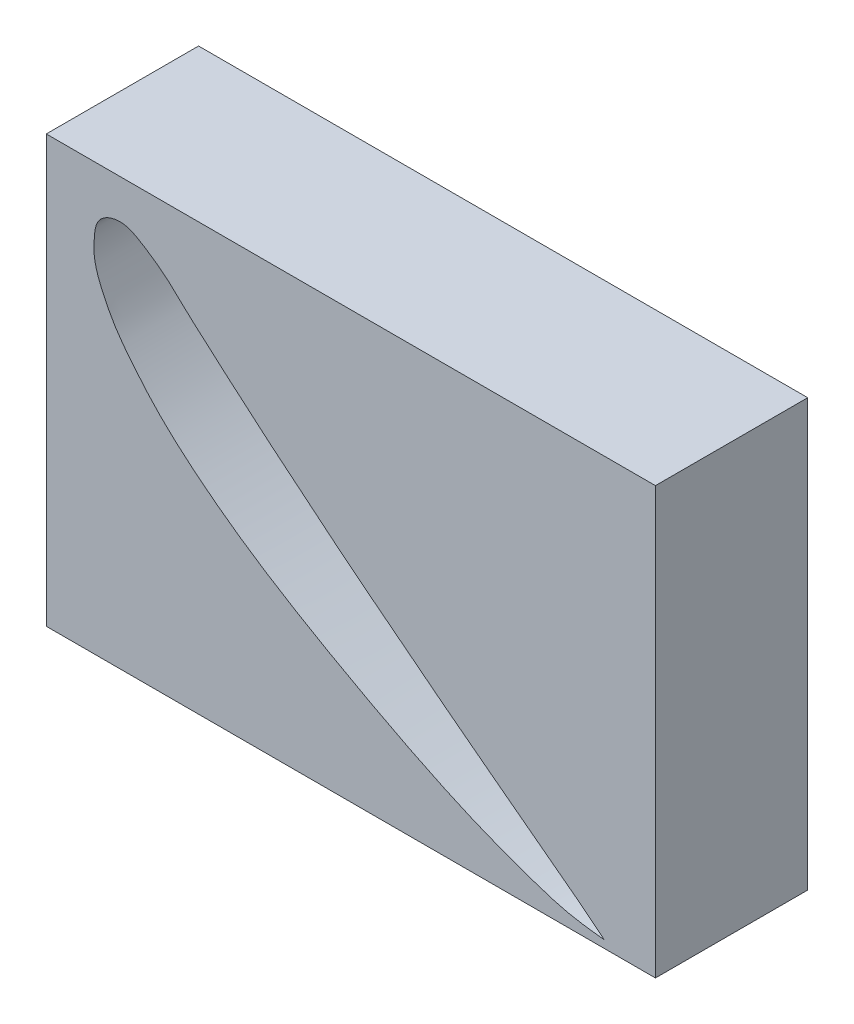
SolidWorks part; units mm, degrees
ref_plane "Přední rovina" through (0, 0, 0) normal (0, 0, 1) x (1, 0, 0)
ref_plane "Horní rovina" through (0, 0, 0) normal (0, 1, 0) x (1, 0, 0)
ref_plane "Pravá rovina" through (0, 0, 0) normal (1, 0, 0) x (0, 0, -1)
sketch "Skica1" plane through (0, 0, 0) normal (0, 0, 1) x (1, 0, 0)
  line L0 (57.6037, -35.5424) -> (61.601, -38.7676) construction
  line L1 (57.6037, -35.5424) -> (61.601, -38.7676)
  spline S0 degree 3 poles (-2246.4894, -4396.8652) (522.6549, -351.0141) (275.9598, -201.8094) (45.3308, -26.2147) (37.1067, -20.0526) (29.0609, -13.6617) (20.9169, -7.398) (12.993, -0.8587) (5.0583, 5.6704) (-1.3799, 11.3186) (-6.5541, 15.8204) (-9.5724, 18.8723) (-12.2988, 20.9767) (-14.4636, 22.3926) (-16.5102, 23.5175) (-19.0351, 23.6655) (-21.8604, 22.3396) (-22.1349, 19.2816) (-22.2372, 16.5185) (-21.5273, 13.8354) (-20.2845, 11.1357) (-18.5799, 7.8791) (-15.8508, 4.352) (-11.3474, -0.934) (-4.8703, -6.6445) (3.4492, -12.7373) (12.263, -18.1725) (21.3286, -23.2931) (30.6182, -28.1714) (40.2405, -32.7083) (48.6641, -35.8531) (111.4267, -55.7376) (210.4243, 115.9494) (-786.2505, -4962.4194) knots -4.030237 -4.030237 -4.030237 -4.030237 0.024539 0.073618 0.122696 0.171758 0.22082 0.269879 0.318937 0.368025 0.392583 0.417173 0.42944 0.441765 0.454461 0.461994 0.477713 0.492781 0.502278 0.517832 0.531656 0.544957 0.570361 0.595284 0.64443 0.693536 0.742943 0.792666 0.842691 0.89326 0.944916 0.971522 1.833313 1.833313 1.833313 1.833313 only from (57.6037, -35.5424) to (61.601, -38.7676) construction
  spline S1 degree 3 poles (57.6037, -35.5424) (56.2389, -34.5075) (52.1446, -31.4026) (45.3308, -26.2147) (37.1067, -20.0526) (29.0609, -13.6617) (20.9169, -7.398) (12.993, -0.8587) (5.0583, 5.6704) (-1.3799, 11.3186) (-6.5541, 15.8204) (-9.5724, 18.8723) (-12.2988, 20.9767) (-14.4636, 22.3926) (-16.5102, 23.5175) (-19.0351, 23.6655) (-21.8604, 22.3396) (-22.1349, 19.2816) (-22.2372, 16.5185) (-21.5273, 13.8354) (-20.2845, 11.1357) (-18.5799, 7.8791) (-15.8508, 4.352) (-11.3474, -0.934) (-4.8703, -6.6445) (3.4492, -12.7373) (12.263, -18.1725) (21.3286, -23.2931) (30.6182, -28.1714) (40.2405, -32.7083) (48.6641, -35.8531) (55.7905, -38.1109) (59.6208, -38.5438) (61.601, -38.7676) knots 0 0 0 0 0.024539 0.073618 0.122696 0.171758 0.22082 0.269879 0.318937 0.368025 0.392583 0.417173 0.42944 0.441765 0.454461 0.461994 0.477713 0.492781 0.502278 0.517832 0.531656 0.544957 0.570361 0.595284 0.64443 0.693536 0.742943 0.792666 0.842691 0.89326 0.944916 0.971522 1 1 1 1
sketch "Skica2" plane through (0, 0, -25) normal (0, 0, 1) x (1, 0, 0)
  line L0 (49.5324, -35.4099) -> (52.1971, -38.4061) construction
  line L1 (49.5324, -35.4099) -> (52.1971, -38.4061)
  spline S0 degree 3 poles (-2422.1261, -4356.754) (119.4602, -484.6473) (198.5669, -183.8266) (44.0381, -29.8369) (42.63, -28.4665) (39.7718, -25.7548) (38.3203, -24.4152) (35.3911, -21.743) (33.915, -20.4084) (30.9514, -17.7269) (29.4613, -16.3837) (26.4471, -13.7142) (24.9198, -12.392) (21.8445, -9.7462) (20.298, -8.4208) (17.2127, -5.7327) (15.6677, -4.3695) (12.5956, -1.6516) (11.0641, -0.2982) (8.0191, 2.4064) (6.5076, 3.7595) (3.5299, 6.4916) (2.0638, 7.8707) (-0.1131, 9.9471) (-0.8345, 10.6399) (-2.2678, 12.022) (-2.9816, 12.7104) (-4.0303, 13.755) (-4.3761, 14.1052) (-5.0571, 14.8128) (-5.3913, 15.1709) (-6.3841, 16.2506) (-7.0355, 16.9761) (-8.3961, 18.3583) (-9.111, 19.0087) (-10.2325, 19.9233) (-10.6147, 20.2185) (-11.1984, 20.6452) (-11.3945, 20.7849) (-11.7903, 21.0582) (-11.9904, 21.1914) (-12.6095, 21.5646) (-13.0434, 21.7767) (-13.7562, 21.9544) (-14.0033, 21.99) (-14.4949, 22.0119) (-14.7422, 21.999) (-15.2396, 21.9277) (-15.4895, 21.8691) (-15.9706, 21.7107) (-16.2046, 21.6107) (-16.6572, 21.3608) (-16.8695, 21.2139) (-17.1572, 20.9564) (-17.2489, 20.8632) (-17.4158, 20.6675) (-17.4914, 20.565) (-17.6989, 20.2462) (-17.8121, 20.0162) (-17.9984, 19.5538) (-18.0729, 19.3196) (-18.2023, 18.8482) (-18.257, 18.6109) (-18.3592, 18.135) (-18.408, 17.8967) (-18.541, 17.1794) (-18.6077, 16.6987) (-18.6457, 15.751) (-18.6235, 15.2814) (-18.5201, 14.3482) (-18.4383, 13.8842) (-18.2361, 12.9768) (-18.115, 12.5308) (-17.8479, 11.6477) (-17.7028, 11.2103) (-17.3975, 10.3403) (-17.2355, 9.9084) (-16.8829, 9.0546) (-16.6911, 8.6333) (-16.276, 7.8013) (-16.055, 7.3933) (-15.3639, 6.1896) (-14.8648, 5.4122) (-13.322, 3.1016) (-12.2239, 1.597) (-10.4033, -0.5618) (-9.7697, -1.2667) (-8.4544, -2.6525) (-7.7707, -3.3353) (-5.6726, -5.3393) (-4.2154, -6.6181) (-1.2125, -9.0994) (0.3356, -10.2987) (3.5181, -12.6263) (5.1535, -13.7534) (8.4948, -15.9584) (10.2059, -17.04) (15.3343, -20.2067) (18.7683, -22.2282) (23.9059, -25.1912) (25.617, -26.1657) (29.0369, -28.0864) (30.745, -29.034) (33.3103, -30.4226) (34.1675, -30.8806) (35.8693, -31.7743) (36.7155, -32.2108) (39.2406, -33.4849) (40.9056, -34.2889) (43.3709, -35.4374) (44.1872, -35.8107) (45.8085, -36.5389) (46.6139, -36.8924) (47.8244, -37.3526) (48.2284, -37.4942) (49.039, -37.7426) (49.443, -37.8493) (87.7994, -46.8706) (93.209, 57.2465) (268.8399, -5032.359) knots -3.415804 -3.415804 -3.415804 -3.415804 0.03125 0.03125 0.0625 0.0625 0.09375 0.09375 0.125 0.125 0.15625 0.15625 0.1875 0.1875 0.21875 0.21875 0.25 0.25 0.28125 0.28125 0.3125 0.3125 0.34375 0.34375 0.359375 0.359375 0.375 0.375 0.382813 0.382813 0.390625 0.390625 0.40625 0.40625 0.421875 0.421875 0.429688 0.429688 0.433594 0.433594 0.4375 0.4375 0.445313 0.445313 0.449219 0.449219 0.453125 0.453125 0.457031 0.457031 0.460938 0.460938 0.464844 0.464844 0.466797 0.466797 0.46875 0.46875 0.472656 0.472656 0.476563 0.476563 0.480469 0.480469 0.484375 0.484375 0.492188 0.492188 0.5 0.5 0.507813 0.507813 0.515625 0.515625 0.523438 0.523438 0.53125 0.53125 0.539063 0.539063 0.546875 0.546875 0.5625 0.5625 0.59375 0.59375 0.609375 0.609375 0.625 0.625 0.65625 0.65625 0.6875 0.6875 0.71875 0.71875 0.75 0.75 0.8125 0.8125 0.84375 0.84375 0.875 0.875 0.890625 0.890625 0.90625 0.90625 0.9375 0.9375 0.953125 0.953125 0.96875 0.96875 0.976563 0.976563 0.984375 0.984375 1.726938 1.726938 1.726938 1.726938 only from (49.5324, -35.4099) to (52.1971, -38.4061) construction
  spline S1 degree 3 poles (49.5324, -35.4099) (48.1839, -33.9995) (46.8147, -32.6039) (44.0381, -29.8369) (42.63, -28.4665) (39.7718, -25.7548) (38.3203, -24.4152) (35.3911, -21.743) (33.915, -20.4084) (30.9514, -17.7269) (29.4613, -16.3837) (26.4471, -13.7142) (24.9198, -12.392) (21.8445, -9.7462) (20.298, -8.4208) (17.2127, -5.7327) (15.6677, -4.3695) (12.5956, -1.6516) (11.0641, -0.2982) (8.0191, 2.4064) (6.5076, 3.7595) (3.5299, 6.4916) (2.0638, 7.8707) (-0.1131, 9.9471) (-0.8345, 10.6399) (-2.2678, 12.022) (-2.9816, 12.7104) (-4.0303, 13.755) (-4.3761, 14.1052) (-5.0571, 14.8128) (-5.3913, 15.1709) (-6.3841, 16.2506) (-7.0355, 16.9761) (-8.3961, 18.3583) (-9.111, 19.0087) (-10.2325, 19.9233) (-10.6147, 20.2185) (-11.1984, 20.6452) (-11.3945, 20.7849) (-11.7903, 21.0582) (-11.9904, 21.1914) (-12.6095, 21.5646) (-13.0434, 21.7767) (-13.7562, 21.9544) (-14.0033, 21.99) (-14.4949, 22.0119) (-14.7422, 21.999) (-15.2396, 21.9277) (-15.4895, 21.8691) (-15.9706, 21.7107) (-16.2046, 21.6107) (-16.6572, 21.3608) (-16.8695, 21.2139) (-17.1572, 20.9564) (-17.2489, 20.8632) (-17.4158, 20.6675) (-17.4914, 20.565) (-17.6989, 20.2462) (-17.8121, 20.0162) (-17.9984, 19.5538) (-18.0729, 19.3196) (-18.2023, 18.8482) (-18.257, 18.6109) (-18.3592, 18.135) (-18.408, 17.8967) (-18.541, 17.1794) (-18.6077, 16.6987) (-18.6457, 15.751) (-18.6235, 15.2814) (-18.5201, 14.3482) (-18.4383, 13.8842) (-18.2361, 12.9768) (-18.115, 12.5308) (-17.8479, 11.6477) (-17.7028, 11.2103) (-17.3975, 10.3403) (-17.2355, 9.9084) (-16.8829, 9.0546) (-16.6911, 8.6333) (-16.276, 7.8013) (-16.055, 7.3933) (-15.3639, 6.1896) (-14.8648, 5.4122) (-13.322, 3.1016) (-12.2239, 1.597) (-10.4033, -0.5618) (-9.7697, -1.2667) (-8.4544, -2.6525) (-7.7707, -3.3353) (-5.6726, -5.3393) (-4.2154, -6.6181) (-1.2125, -9.0994) (0.3356, -10.2987) (3.5181, -12.6263) (5.1535, -13.7534) (8.4948, -15.9584) (10.2059, -17.04) (15.3343, -20.2067) (18.7683, -22.2282) (23.9059, -25.1912) (25.617, -26.1657) (29.0369, -28.0864) (30.745, -29.034) (33.3103, -30.4226) (34.1675, -30.8806) (35.8693, -31.7743) (36.7155, -32.2108) (39.2406, -33.4849) (40.9056, -34.2889) (43.3709, -35.4374) (44.1872, -35.8107) (45.8085, -36.5389) (46.6139, -36.8924) (47.8244, -37.3526) (48.2284, -37.4942) (49.039, -37.7426) (49.443, -37.8493) (50.6411, -38.1311) (51.4253, -38.2689) (52.1971, -38.4061) knots 0 0 0 0 0.03125 0.03125 0.0625 0.0625 0.09375 0.09375 0.125 0.125 0.15625 0.15625 0.1875 0.1875 0.21875 0.21875 0.25 0.25 0.28125 0.28125 0.3125 0.3125 0.34375 0.34375 0.359375 0.359375 0.375 0.375 0.382813 0.382813 0.390625 0.390625 0.40625 0.40625 0.421875 0.421875 0.429688 0.429688 0.433594 0.433594 0.4375 0.4375 0.445313 0.445313 0.449219 0.449219 0.453125 0.453125 0.457031 0.457031 0.460938 0.460938 0.464844 0.464844 0.466797 0.466797 0.46875 0.46875 0.472656 0.472656 0.476563 0.476563 0.480469 0.480469 0.484375 0.484375 0.492188 0.492188 0.5 0.5 0.507813 0.507813 0.515625 0.515625 0.523438 0.523438 0.53125 0.53125 0.539063 0.539063 0.546875 0.546875 0.5625 0.5625 0.59375 0.59375 0.609375 0.609375 0.625 0.625 0.65625 0.65625 0.6875 0.6875 0.71875 0.71875 0.75 0.75 0.8125 0.8125 0.84375 0.84375 0.875 0.875 0.890625 0.890625 0.90625 0.90625 0.9375 0.9375 0.953125 0.953125 0.96875 0.96875 0.976563 0.976563 0.984375 0.984375 1 1 1 1
sketch "Skica3" plane through (0, 0, -25) normal (0, 0, 1) x (1, 0, 0)
  line L1 (-30, 30) -> (70, 30)
  line L2 (-30, 30) -> (-30, -40)
  line L3 (-30, -40) -> (70, -40)
  line L4 (70, 30) -> (70, -40)
  dimension "D1" = 30
  dimension "D2" = 40
  dimension "D3" = 30
  dimension "D4" = 70
extrude "Přidat vysunutím1" add sketch "Skica3" along normal up to surface (25 mm away)
extrude "Odebrat vysunutím1" cut sketch "Skica1" against normal through all
